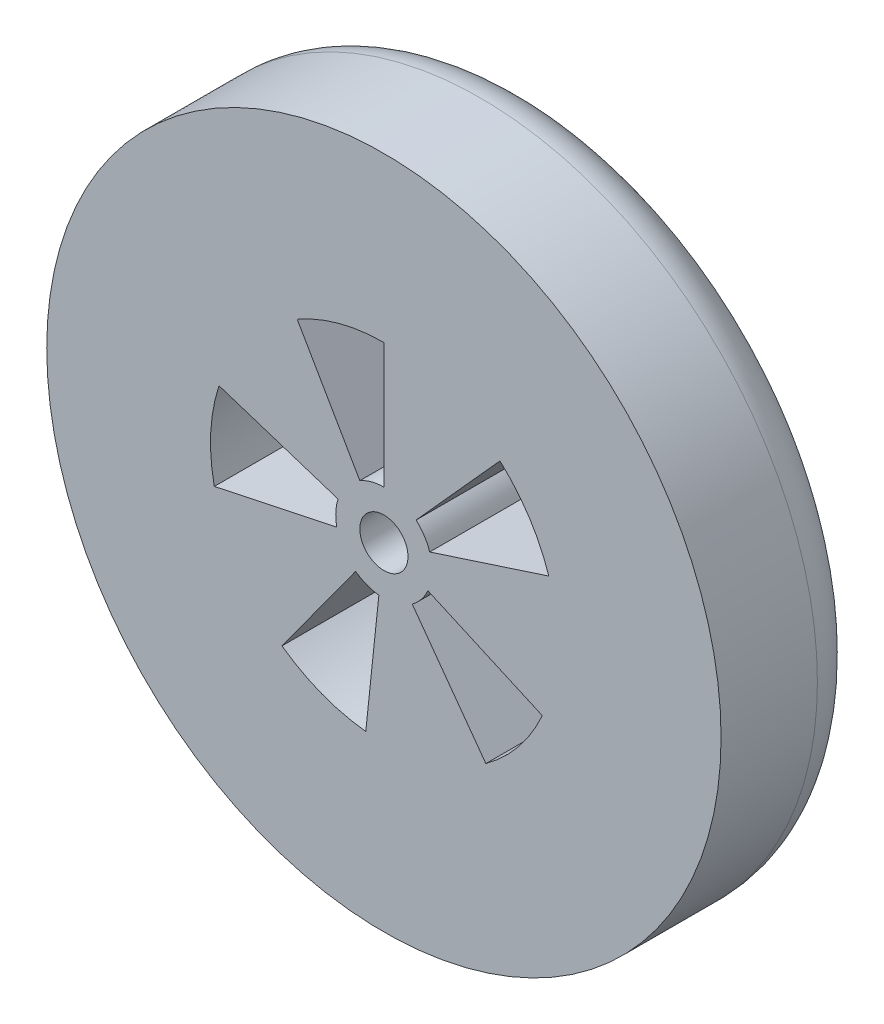
SolidWorks part; units mm, degrees
ref_plane "Front Plane" through (0, 0, 0) normal (0, 0, 1) x (1, 0, 0)
ref_plane "Top Plane" through (0, 0, 0) normal (0, 1, 0) x (1, 0, 0)
ref_plane "Right Plane" through (0, 0, 0) normal (1, 0, 0) x (0, 0, -1)
sketch "Sketch1" plane through (0, 0, 0) normal (0, 0, 1) x (1, 0, 0)
  circle A0 centre (0, 0) radius 35
  dimension "D1" = 70
extrude "Boss-Extrude1" add sketch "Sketch1" along normal blind 15
sketch "Sketch2" plane through (0, 0, 0) normal (0, 0, -1) x (-1, 0, 0)
  circle A0 centre (0, 0) radius 20
  dimension "D1" = 40
extrude "Cut-Extrude1" cut sketch "Sketch2" against normal blind 3
fillet "Fillet2" radius 2 1 edges at (-20, 0, 3)
sketch "Sketch4" plane through (0, 0, 3) normal (0, 0, -1) x (-1, 0, 0)
  circle A0 centre (0, 0) radius 2.5
  dimension "D1" = 5
extrude "Cut-Extrude2" cut sketch "Sketch4" against normal through all
sketch "Sketch5" plane through (0, 0, 3) normal (0, 0, -1) x (-1, 0, 0)
  line L0 (0, 5) -> (0, 18)
  line L1 (2.5, 4.3301) -> (9, 15.5885)
  line L2 (4.8907, -1.0396) -> (17.6067, -3.7424)
  line L3 (4.7553, 1.5451) -> (17.119, 5.5623)
  line L4 (0.5226, -4.9726) -> (1.8815, -17.9014)
  line L5 (2.9389, -4.0451) -> (10.5801, -14.5623)
  line L6 (-4.5677, -2.0337) -> (-16.4438, -7.3213)
  line L7 (-2.9389, -4.0451) -> (-10.5801, -14.5623)
  line L8 (-3.3457, 3.7157) -> (-12.0444, 13.3766)
  line L9 (-4.7553, 1.5451) -> (-17.119, 5.5623)
  circle A0 centre (0, 0) radius 5 construction
  circle A1 centre (0, 0) radius 18 construction
  circle A2 centre (0, 0) radius 18 construction
  arc A3 (0, 18) -> (9, 15.5885) centre (0, 0) cw
  arc A4 (0, 5) -> (2.5, 4.3301) centre (0, 0) cw
  arc A5 (17.119, 5.5623) -> (17.6067, -3.7424) centre (0, 0) cw
  arc A6 (4.7553, 1.5451) -> (4.8907, -1.0396) centre (0, 0) cw
  arc A7 (10.5801, -14.5623) -> (1.8815, -17.9014) centre (0, 0) cw
  arc A8 (2.9389, -4.0451) -> (0.5226, -4.9726) centre (0, 0) cw
  arc A9 (-10.5801, -14.5623) -> (-16.4438, -7.3213) centre (0, 0) cw
  arc A10 (-2.9389, -4.0451) -> (-4.5677, -2.0337) centre (0, 0) cw
  arc A11 (-17.119, 5.5623) -> (-12.0444, 13.3766) centre (0, 0) cw
  arc A12 (-4.7553, 1.5451) -> (-3.3457, 3.7157) centre (0, 0) cw
  point P34 (0, 0)
  dimension "D1" = 10
  dimension "D2" = 30
  dimension "D3" = 5
extrude "Cut-Extrude3" cut sketch "Sketch5" against normal through all
fillet "Fillet3" radius 5 1 edges at (35, 0, 0)
